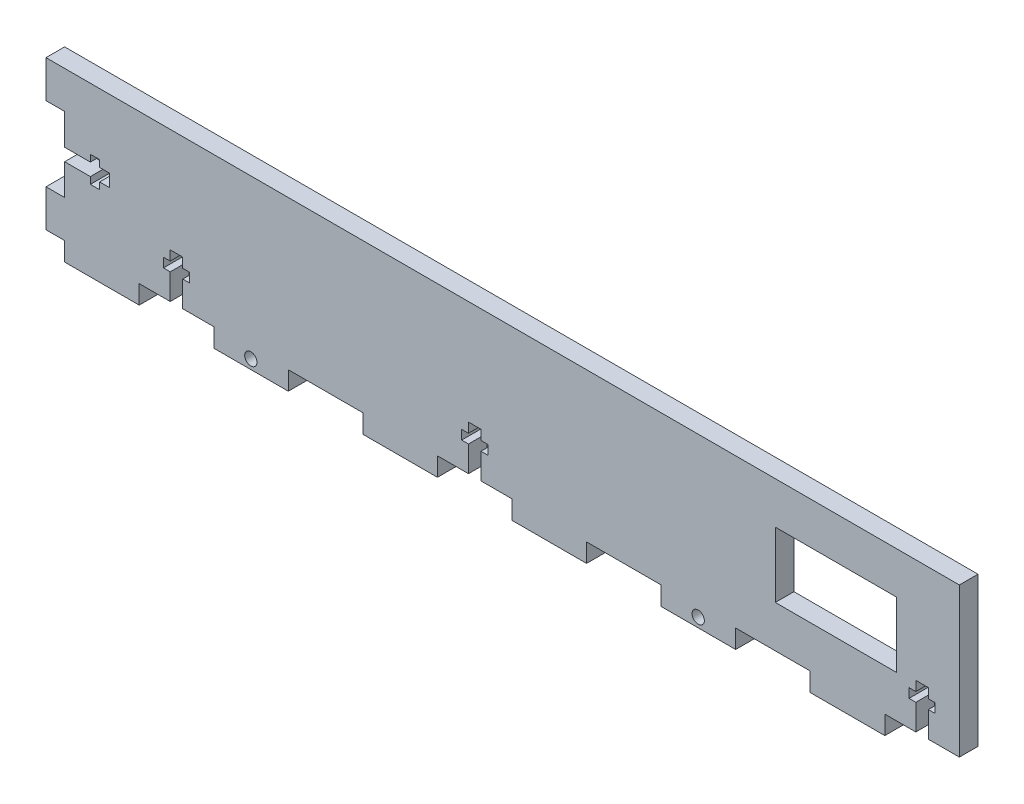
SolidWorks part; units mm, degrees
ref_plane "Front Plane" through (0, 0, 0) normal (0, 0, 1) x (1, 0, 0)
ref_plane "Top Plane" through (0, 0, 0) normal (0, 1, 0) x (1, 0, 0)
ref_plane "Right Plane" through (0, 0, 0) normal (1, 0, 0) x (0, 0, -1)
sketch "Sketch1" plane through (0, 0, 0) normal (0, 0, 1) x (1, 0, 0)
  line L0 (-262.733, -49.2353) -> (-262.733, 69.85) construction
  line L1 (42.067, 25.4) -> (-262.733, 25.4)
  line L2 (42.067, 25.4) -> (42.067, -25.4)
  line L3 (42.067, -25.4) -> (-262.733, -25.4)
  line L4 (-262.733, 25.4) -> (-262.733, -25.4)
  line L5 (63.0291, 0) -> (-62.7737, 0) construction
  line L6 (-19.6295, 10.033) -> (19.6295, 10.033) construction
  line L7 (19.6295, -10.033) -> (-19.6295, -10.033) construction
  line L8 (27.25, 6.27) -> (27.25, 8.0899) construction
  dimension "D1" = 50.8
  dimension "D2" = 14.817
extrude "Boss-Extrude1" add sketch "Sketch1" along normal blind 6.35
sketch "Sketch2" plane through (0, 0, 6.35) normal (0, 0, 1) x (1, 0, 0)
  line L0 (-41.9443, 0) -> (30.2812, 0) construction
  line L1 (-20.6375, 11.1125) -> (20.6375, 11.1125)
  line L2 (-20.6375, 11.1125) -> (-20.6375, -11.1125)
  line L3 (-20.6375, -11.1125) -> (20.6375, -11.1125)
  line L4 (20.6375, 11.1125) -> (20.6375, -11.1125)
  line L5 (-19.6295, 10.033) -> (19.6295, 10.033) construction
  line L6 (19.6295, -10.033) -> (-19.6295, -10.033) construction
  line L7 (0, 34.6052) -> (0, -28.4279) construction
  line L8 (-20.1295, -9.533) -> (-20.1295, 9.533) construction
  line L9 (20.1295, 9.533) -> (20.1295, -9.533) construction
  dimension "D1" = 22.225
  dimension "D2" = 41.275
extrude "Cut-Extrude1" cut sketch "Sketch2" against normal through all
ref_plane "Plane1" through (42.067, -25.4, 6.35) normal (1, 0, 0) x (0, 0, -1)
sketch "Sketch5" plane through (0, -25.4, 0) normal (0, -1, 0) x (1, 0, 0)
  line L0 (-262.733, 6.35) -> (42.067, 6.35) construction
  line L1 (16.667, 6.35) -> (-8.733, 6.35)
  line L2 (16.667, 6.35) -> (16.667, 0)
  line L3 (16.667, 0) -> (-8.733, 0)
  line L4 (-8.733, 6.35) -> (-8.733, 0)
  line L5 (-262.733, 0) -> (42.067, 0) construction
  dimension "D1" = 25.4
  dimension "D2" = 25.4
extrude "Boss-Extrude2" add sketch "Sketch5" along normal blind 6.35
pattern_linear "LPattern1" count 6 spacing 50.8 along (-1, 0, 0) of "Boss-Extrude2"
sketch "Sketch6" plane through (-262.733, 0, 0) normal (-1, 0, 0) x (0, 0, 1)
  line L0 (0, 25.4) -> (6.35, 25.4)
  line L1 (6.35, 25.4) -> (6.35, 12.7)
  line L2 (6.35, 25.4) -> (6.35, -31.75) construction
  line L3 (6.35, 12.7) -> (0, 12.7)
  line L4 (0, 25.4) -> (0, -31.75) construction
  line L5 (0, 12.7) -> (0, 25.4)
  dimension "D1" = 12.7
extrude "Boss-Extrude3" add sketch "Sketch6" along normal blind 6.35
pattern_linear "LPattern2" count 2 spacing 38.1 along (0, -1, 0) of "Boss-Extrude3"
sketch "Sketch7" plane through (0, 0, 6.35) normal (0, 0, 1) x (1, 0, 0)
  line L0 (-257.1687, 0) -> (-223.3079, 0) construction
  line L1 (-269.083, 12.7) -> (-262.733, 12.7) construction
  line L2 (-269.083, -12.7) -> (-262.733, -12.7) construction
  line L3 (-262.733, 12.7) -> (-262.733, -12.7) construction
  line B0 (-262.733, 2.1336) -> (-262.733, -2.1336)
  line B1 (-250.795, -2.1336) -> (-250.795, -4.445)
  line B2 (-250.795, -4.445) -> (-253.97, -4.445)
  line B3 (-253.97, -4.445) -> (-253.97, -2.1336)
  line B4 (-253.97, -2.1336) -> (-262.733, -2.1336)
  line B5 (-250.795, -2.1336) -> (-247.493, -2.1336)
  line B6 (-247.493, -2.1336) -> (-247.493, 2.1336)
  line B7 (-250.795, 2.1336) -> (-247.493, 2.1336)
  line B8 (-253.97, 2.1336) -> (-262.733, 2.1336)
  line B9 (-253.97, 4.445) -> (-253.97, 2.1336)
  line B10 (-250.795, 4.445) -> (-253.97, 4.445)
  line B11 (-250.795, 2.1336) -> (-250.795, 4.445)
sketch_block_instance "TSlot-1"
sketch_block "TSlot" parameters "D1"=3.302, "D2"=3.175
extrude "Cut-Extrude2" cut sketch "Sketch7" against normal through all
sketch "Sketch8" plane through (0, 0, 6.35) normal (0, 0, 1) x (1, 0, 0)
  line L0 (29.367, -1.7985) -> (29.367, -25.4) construction
  line L1 (16.667, -25.4) -> (42.067, -25.4) construction
  line L2 (42.067, -25.4) -> (42.067, 25.4) construction
  line L3 (16.667, -31.75) -> (16.667, -25.4) construction
  line L4 (-224.633, 2.3642) -> (-224.633, -25.4) construction
  line L5 (-237.333, -25.4) -> (-211.933, -25.4) construction
  line L6 (-237.333, -31.75) -> (-237.333, -25.4) construction
  line L7 (-211.933, -31.75) -> (-211.933, -25.4) construction
  line L8 (-123.033, 2.3642) -> (-123.033, -25.4) construction
  line L9 (-135.733, -25.4) -> (-110.333, -25.4) construction
  line L10 (-135.733, -31.75) -> (-135.733, -25.4) construction
  line L11 (-110.333, -31.75) -> (-110.333, -25.4) construction
  line B0 (-226.7666, -25.4) -> (-222.4994, -25.4)
  line B1 (-222.4994, -13.462) -> (-220.188, -13.462)
  line B2 (-220.188, -13.462) -> (-220.188, -16.637)
  line B3 (-220.188, -16.637) -> (-222.4994, -16.637)
  line B4 (-222.4994, -16.637) -> (-222.4994, -25.4)
  line B5 (-222.4994, -13.462) -> (-222.4994, -10.16)
  line B6 (-222.4994, -10.16) -> (-226.7666, -10.16)
  line B7 (-226.7666, -13.462) -> (-226.7666, -10.16)
  line B8 (-226.7666, -16.637) -> (-226.7666, -25.4)
  line B9 (-229.078, -16.637) -> (-226.7666, -16.637)
  line B10 (-229.078, -13.462) -> (-229.078, -16.637)
  line B11 (-226.7666, -13.462) -> (-229.078, -13.462)
  line B12 (-125.1666, -25.4) -> (-120.8994, -25.4)
  line B13 (-120.8994, -13.462) -> (-118.588, -13.462)
  line B14 (-118.588, -13.462) -> (-118.588, -16.637)
  line B15 (-118.588, -16.637) -> (-120.8994, -16.637)
  line B16 (-120.8994, -16.637) -> (-120.8994, -25.4)
  line B17 (-120.8994, -13.462) -> (-120.8994, -10.16)
  line B18 (-120.8994, -10.16) -> (-125.1666, -10.16)
  line B19 (-125.1666, -13.462) -> (-125.1666, -10.16)
  line B20 (-125.1666, -16.637) -> (-125.1666, -25.4)
  line B21 (-127.478, -16.637) -> (-125.1666, -16.637)
  line B22 (-127.478, -13.462) -> (-127.478, -16.637)
  line B23 (-125.1666, -13.462) -> (-127.478, -13.462)
  line B24 (27.2334, -25.4) -> (31.5006, -25.4)
  line B25 (31.5006, -13.462) -> (33.812, -13.462)
  line B26 (33.812, -13.462) -> (33.812, -16.637)
  line B27 (33.812, -16.637) -> (31.5006, -16.637)
  line B28 (31.5006, -16.637) -> (31.5006, -25.4)
  line B29 (31.5006, -13.462) -> (31.5006, -10.16)
  line B30 (31.5006, -10.16) -> (27.2334, -10.16)
  line B31 (27.2334, -13.462) -> (27.2334, -10.16)
  line B32 (27.2334, -16.637) -> (27.2334, -25.4)
  line B33 (24.922, -16.637) -> (27.2334, -16.637)
  line B34 (24.922, -13.462) -> (24.922, -16.637)
  line B35 (27.2334, -13.462) -> (24.922, -13.462)
sketch_block_instance "TSlot-2"
sketch_block_instance "TSlot-4"
sketch_block_instance "TSlot-5"
extrude "Cut-Extrude3" cut sketch "Sketch8" against normal through all
sketch "Sketch9" plane through (0, 0, 0) normal (0, 0, -1) x (-1, 0, 0)
  line L0 (44.7707, -31.75) -> (49.0379, -25.4) construction
  line L1 (59.533, -31.75) -> (34.133, -31.75) construction
  line L2 (44.7707, -31.75) -> (44.7707, -25.4) construction
  line L3 (49.0379, -31.75) -> (44.7707, -25.4) construction
  line L4 (49.0379, -25.4) -> (49.0379, -31.75) construction
  line L5 (197.1707, -31.75) -> (201.4379, -25.4) construction
  line L6 (197.1707, -31.75) -> (197.1707, -25.4) construction
  line L7 (211.933, -31.75) -> (186.533, -31.75) construction
  line L8 (201.4379, -31.75) -> (197.1707, -25.4) construction
  line L9 (201.4379, -25.4) -> (201.4379, -31.75) construction
  circle A0 centre (46.9043, -28.575) radius 2.0955
  circle A1 centre (199.3043, -28.575) radius 2.0955
  dimension "D1" = 4.191
extrude "Cut-Extrude4" cut sketch "Sketch9" against normal through all
